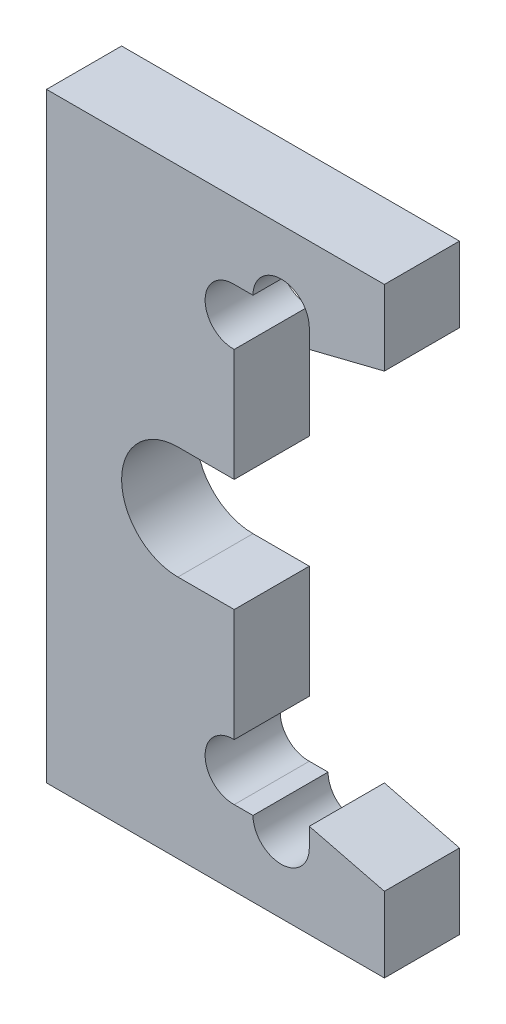
SolidWorks part; units mm, degrees
ref_plane "Front Plane" through (0, 0, 0) normal (0, 0, 1) x (1, 0, 0)
ref_plane "Top Plane" through (0, 0, 0) normal (0, 1, 0) x (1, 0, 0)
ref_plane "Right Plane" through (0, 0, 0) normal (1, 0, 0) x (0, 0, -1)
sketch "Sketch1" plane through (0, 0, 0) normal (0, 0, 1) x (1, 0, 0)
  line L0 (13.3682, 13.3771) -> (4.3682, 13.3771)
  line L1 (11.3682, 11.3771) -> (11.3682, 10.8771)
  line L2 (11.3682, 10.8771) -> (13.3682, 11.3771)
  line L3 (13.3682, 11.3771) -> (13.3682, 13.3771)
  line L4 (9.3682, 5.3771) -> (-1.8092, 5.3771) construction
  line L6 (4.3682, 13.3771) -> (4.3682, 5.3771)
  line L7 (11.3682, 11.3771) -> (9.3682, 11.3771) construction
  line L8 (9.3682, 11.3771) -> (9.3682, 9.878) construction
  line L9 (9.8682, 11.3771) -> (9.3682, 11.3771)
  line L16 (9.3682, 6.8771) -> (7.8682, 6.8771)
  line L17 (9.3682, 9.878) -> (9.3682, 6.8771)
  line L18 (6.3682, 5.3771) -> (4.3682, 5.3771)
  arc A0 (9.3682, 9.878) -> (9.3682, 11.3771) centre (9.3423, 10.6275) cw
  arc A1 (11.3682, 11.3771) -> (9.8682, 11.3771) centre (10.6182, 11.3771) ccw
  arc A3 (7.8682, 6.8771) -> (6.3682, 5.3771) centre (7.8682, 5.3771) ccw
  dimension "D4" = 0.75
  dimension "D5" = 0.75
  dimension "D9" = 1.5
  dimension "D8" = 2
  dimension "D1" = 2
  dimension "D2" = 6
  dimension "D3" = 0.5
  dimension "D6" = 2
  dimension "D7" = 2
  dimension "D10" = 1.5
extrude "Boss-Extrude1" add sketch "Sketch1" along normal blind 2
mirror "Mirror1" about plane through (6.3682, 5.3771, 2) normal (0, 1, 0) of "Boss-Extrude1"
